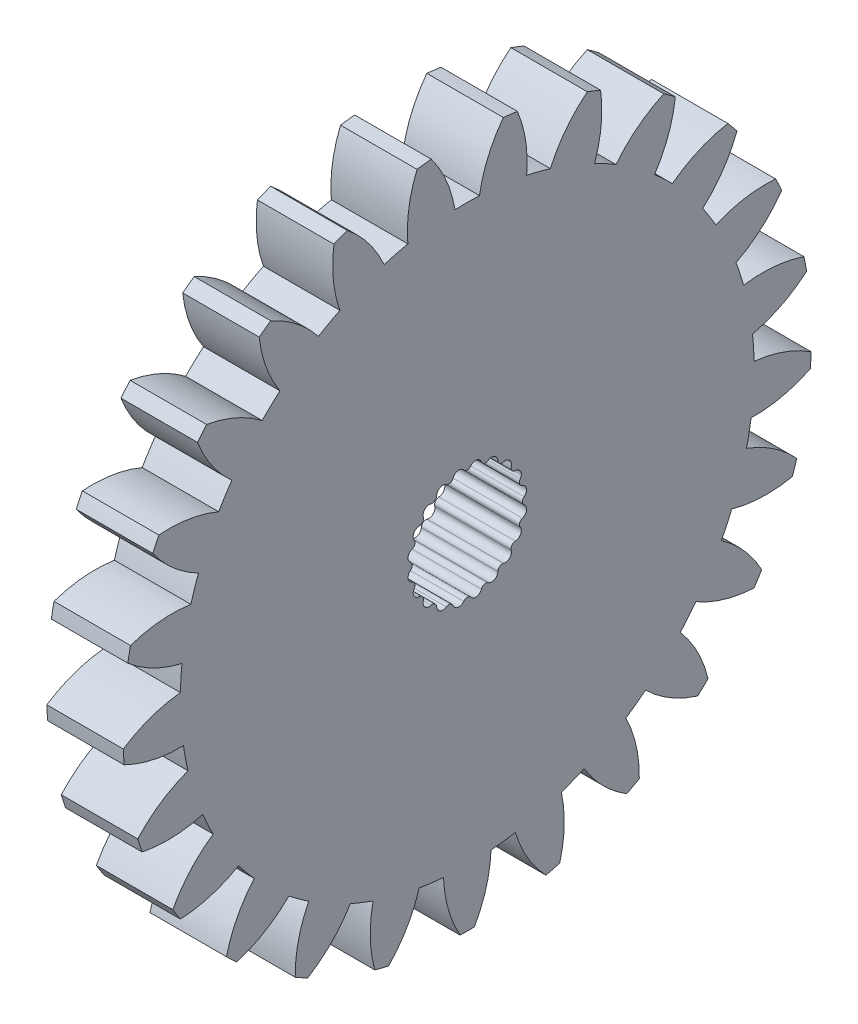
SolidWorks part; units mm, degrees
ref_plane "Plane1" through (0, 0, 0) normal (0, 0, 1) x (1, 0, 0)
ref_plane "Plane2" through (0, 0, 0) normal (0, 1, 0) x (1, 0, 0)
ref_plane "Plane3" through (0, 0, 0) normal (1, 0, 0) x (0, 0, -1)
other "Configuration Table"
sketch "HoldingSke" plane through (0, 0, 0) normal (0, 1, 0) x (1, 0, 0)
  line L0 (0, 0) -> (0.9063, -0.4226)
  line L1 (-15, 0) -> (100, 0) construction
  line L2 (0, 0) -> (-2.1039, 2.3779)
  line L3 (0, 0) -> (-11.863, 4.5341)
  line L4 (0, 0) -> (7.8269, 3.6497)
  line L5 (0, 0) -> (-46.8476, -17.4728)
  line L6 (0, 0) -> (-2.4869, -1.6779)
  line L7 (-2.1039, 2.3779) -> (8.6586, 51.2059)
  line L8 (-76.2, 54.61) -> (-75.3, 54.61)
  line L9 (-71.009, 38.7566) -> (-53.1078, 45.2721)
  line L10 (-76.2, 71.12) -> (104.1128, 71.12)
  line L11 (0, 0) -> (-3, 0)
  line L12 (-76.2, 101.6) -> (-76.162, 101.6)
  line L13 (24.9733, 27.94) -> (52.9518, 28.4284)
  line L14 (24.9733, 27.94) -> (24.9743, 27.94)
  line L15 (24.9733, 27.94) -> (100.4006, 29.5858)
  line L16 (-63.627, -1) -> (-12.827, -1)
  circle A0 centre (0, 0) radius 2.5
  circle A1 centre (0, 0) radius 11.249
  circle A2 centre (0, 0) radius 37.5
  circle A3 centre (0, 0) radius 2.5
  dimension "MHD" = 22.498
  dimension "Hub_dia" = 75
  dimension "Bore" = 5
  dimension "MBD" = 5
  dimension "Num_teeth" = 25
  dimension "Pitch" = 1
  dimension "Overall_len" = 50
  dimension "Show_teeth" = 25
  dimension "Thickness" = 3
  dimension "OAL" = 50.0001
  dimension "T_dim" = 0.9
  dimension "Ap" = 20
  dimension "H" = 19.05
  dimension "Pitch_radius" = 180.3128
  dimension "Width" = 3
  dimension "Backlash" = 0.038
  dimension "Addendum_fac" = 1
  dimension "Dedendum_fac" = 1.25
  dimension "Clearance_fac" = 0.25
  dimension "Dedendum_add" = 0.001
  dimension "Module" = 1
sketch "BasProSke" plane through (0, 0, 0) normal (0, 1, 0) x (1, 0, 0)
  line L0 (-10, 0) -> (60, 0) construction
  line L1 (0, 0) -> (0, 13.5)
  line L2 (0, 0) -> (3, 0)
  line L3 (3, 0) -> (3, 13.5)
  line L4 (3, 13.5) -> (0, 13.5)
  dimension "Thickness" = 3
  dimension "Diameter" = 27
revolve "Base-Revolve" add sketch "BasProSke" angle 360 about L0
sketch "TooCutSke" plane through (0, 0, 0) normal (1, 0, 0) x (0, 0, -1)
  line L1 (0, 0) -> (0, 107) construction
  line L2 (0, 0) -> (-0.8514, 12.471) construction
  line L3 (0, 0) -> (-3.1282, 24.7619) construction
  line L4 (-0.8514, 12.471) -> (-1.5641, 12.3809) construction
  arc A0 (0.4801, 11.2388) -> (-0.4801, 11.2388) centre (0, 0) ccw
  arc A1 (1.4322, 13.4494) -> (-1.4322, 13.4494) centre (0, 0) ccw
  circle A2 centre (0, 0) radius 12.5 construction
  circle A3 centre (0, 0) radius 11.7462 construction
  arc A4 (-0.4801, 11.2388) -> (-1.4322, 13.4494) centre (-5.4133, 10.4244) ccw
  arc A5 (1.4322, 13.4494) -> (0.4801, 11.2388) centre (5.4133, 10.4244) ccw
  dimension "Root_dia" = 22.498
  dimension "Overcut_dia" = 27.0508
  dimension "Pitch_dia" = 25
  dimension "Base_dia" = 23.4923
  dimension "Flank_rad" = 5
  dimension "Half_ang" = 7.2
  dimension "Half_CT" = 0.7184
extrude "ToothCut" cut sketch "TooCutSke" along normal through all
fillet "Breaks" [suppressed] radius 0.02
fillet "RootFillets" [suppressed] radius 0.251
pattern_circular "TeethCuts" count 25 every 14.4 about axis through (-10, 0, 0) along (1, 0, 0) of "ToothCut", "RootFillets", "Breaks"
sketch "HubNeaOneSke" plane through (0, 0, 0) normal (-1, 0, 0) x (0, 0, 1)
  circle A0 centre (0, 0) radius 11.249
  dimension "Diameter" = 22.498
extrude "HubNearOne" [suppressed] add sketch "HubNeaOneSke" along normal blind 47.0001
sketch "HubNeaBotSke" plane through (0, 0, 0) normal (-1, 0, 0) x (0, 0, 1)
  circle A0 centre (0, 0) radius 11.249
  dimension "Diameter" = 22.498
extrude "HubNearBoth" [suppressed] add sketch "HubNeaBotSke" along normal blind 23.5
ref_plane "FarPln" through (3, 0, 0) normal (1, 0, 0) x (0, 0, -1)
sketch "HubFarSke" plane through (3, 0, 0) normal (1, 0, 0) x (0, 0, -1)
  circle A0 centre (0, 0) radius 11.249
  dimension "Diameter" = 22.498
extrude "HubFar" [suppressed] add sketch "HubFarSke" along normal blind 23.5
sketch "BorSke" plane through (0, 0, 0) normal (1, 0, 0) x (0, 0, -1)
  circle A0 centre (0, 0) radius 2.5
  dimension "Diameter" = 5
extrude "Bore" [suppressed] cut sketch "BorSke" along normal mid plane 100.0001
sketch "KeySke" plane through (0, 0, 0) normal (1, 0, 0) x (0, 0, -1)
  line L0 (-1, 0) -> (-1, 3.4)
  line L1 (-1, 3.4) -> (1, 3.4)
  line L2 (1, 3.4) -> (1, 0)
  line L3 (0, 0) -> (0, 34) construction
  line L4 (-1, 0) -> (1, 0)
  dimension "Offset" = 3.4
  dimension "Width" = 2
extrude "Keyway" [suppressed] cut sketch "KeySke" along normal mid plane 100.0001
pattern_circular "Keyway2" [suppressed] count 2 every 90 about axis through (-10, 0, 0) along (1, 0, 0)
sketch "Sketch1" plane through (3, 0, 0) normal (1, 0, 0) x (0, 0, -1)
  arc A252 (1.6617, 1.6617) -> (1.423, 1.7224) centre (1.4913, 1.4913) ccw
  arc A253 (1.2704, 1.7486) -> (1.423, 1.7224) centre (1.3733, 1.8902) ccw
  arc A254 (1.1984, 1.8855) -> (1.2704, 1.7486) centre (1.3733, 1.8902) ccw
  arc A255 (1.1984, 1.8855) -> (1.0669, 2.0939) centre (0.9575, 1.8792) ccw
  arc A256 (1.0669, 2.0939) -> (0.8211, 2.0778) centre (0.9575, 1.8792) ccw
  arc A257 (0.6679, 2.0556) -> (0.8211, 2.0778) centre (0.722, 2.222) ccw
  arc A258 (0.557, 2.1636) -> (0.6679, 2.0556) centre (0.722, 2.222) ccw
  arc A259 (0.557, 2.1636) -> (0.3676, 2.3211) centre (0.3299, 2.0831) ccw
  arc A260 (0.3676, 2.3211) -> (0.1388, 2.2298) centre (0.3299, 2.0831) ccw
  arc A261 (0, 2.1614) -> (0.1388, 2.2298) centre (0, 2.3364) ccw
  arc A262 (-0.1388, 2.2298) -> (0, 2.1614) centre (0, 2.3364) ccw
  arc A263 (-0.1388, 2.2298) -> (-0.3676, 2.3211) centre (-0.3299, 2.0831) ccw
  arc A264 (-0.3676, 2.3211) -> (-0.557, 2.1636) centre (-0.3299, 2.0831) ccw
  arc A265 (-0.6679, 2.0556) -> (-0.557, 2.1636) centre (-0.722, 2.222) ccw
  arc A266 (-0.8211, 2.0778) -> (-0.6679, 2.0556) centre (-0.722, 2.222) ccw
  arc A267 (-0.8211, 2.0778) -> (-1.0669, 2.0939) centre (-0.9575, 1.8792) ccw
  arc A268 (-1.0669, 2.0939) -> (-1.1984, 1.8855) centre (-0.9575, 1.8792) ccw
  arc A269 (-1.2704, 1.7486) -> (-1.1984, 1.8855) centre (-1.3733, 1.8902) ccw
  arc A270 (-1.423, 1.7224) -> (-1.2704, 1.7486) centre (-1.3733, 1.8902) ccw
  arc A271 (-1.423, 1.7224) -> (-1.6617, 1.6617) centre (-1.4913, 1.4913) ccw
  arc A272 (-1.6617, 1.6617) -> (-1.7224, 1.423) centre (-1.4913, 1.4913) ccw
  arc A273 (-1.7486, 1.2704) -> (-1.7224, 1.423) centre (-1.8902, 1.3733) ccw
  arc A274 (-1.8855, 1.1984) -> (-1.7486, 1.2704) centre (-1.8902, 1.3733) ccw
  arc A275 (-1.8855, 1.1984) -> (-2.0939, 1.0669) centre (-1.8792, 0.9575) ccw
  arc A276 (-2.0939, 1.0669) -> (-2.0778, 0.8211) centre (-1.8792, 0.9575) ccw
  arc A277 (-2.0556, 0.6679) -> (-2.0778, 0.8211) centre (-2.222, 0.722) ccw
  arc A278 (-2.1636, 0.557) -> (-2.0556, 0.6679) centre (-2.222, 0.722) ccw
  arc A279 (-2.1636, 0.557) -> (-2.3211, 0.3676) centre (-2.0831, 0.3299) ccw
  arc A280 (-2.3211, 0.3676) -> (-2.2298, 0.1388) centre (-2.0831, 0.3299) ccw
  arc A281 (-2.1614, 0) -> (-2.2298, 0.1388) centre (-2.3364, 0) ccw
  arc A282 (-2.2298, -0.1388) -> (-2.1614, 0) centre (-2.3364, 0) ccw
  arc A283 (-2.2298, -0.1388) -> (-2.3211, -0.3676) centre (-2.0831, -0.3299) ccw
  arc A284 (-2.3211, -0.3676) -> (-2.1636, -0.557) centre (-2.0831, -0.3299) ccw
  arc A285 (-2.0556, -0.6679) -> (-2.1636, -0.557) centre (-2.222, -0.722) ccw
  arc A286 (-2.0778, -0.8211) -> (-2.0556, -0.6679) centre (-2.222, -0.722) ccw
  arc A287 (-2.0778, -0.8211) -> (-2.0939, -1.0669) centre (-1.8792, -0.9575) ccw
  arc A288 (-2.0939, -1.0669) -> (-2.0547, -1.1225) centre (-1.8792, -0.9575) ccw
  arc A290 (2.0547, 1.1225) -> (1.8855, 1.1984) centre (1.8792, 0.9575) ccw
  arc A291 (1.7486, 1.2704) -> (1.8855, 1.1984) centre (1.8902, 1.3733) ccw
  arc A292 (1.7224, 1.423) -> (1.7486, 1.2704) centre (1.8902, 1.3733) ccw
  arc A293 (1.7224, 1.423) -> (1.6617, 1.6617) centre (1.4913, 1.4913) ccw
  arc A294 (-1.6617, -1.6617) -> (-1.423, -1.7224) centre (-1.4913, -1.4913) ccw
  arc A295 (-1.2704, -1.7486) -> (-1.423, -1.7224) centre (-1.3733, -1.8902) ccw
  arc A296 (-1.1984, -1.8855) -> (-1.2704, -1.7486) centre (-1.3733, -1.8902) ccw
  arc A297 (-1.1984, -1.8855) -> (-1.0669, -2.0939) centre (-0.9575, -1.8792) ccw
  arc A298 (-1.0669, -2.0939) -> (-0.8211, -2.0778) centre (-0.9575, -1.8792) ccw
  arc A299 (-0.6679, -2.0556) -> (-0.8211, -2.0778) centre (-0.722, -2.222) ccw
  arc A300 (-0.557, -2.1636) -> (-0.6679, -2.0556) centre (-0.722, -2.222) ccw
  arc A301 (-0.557, -2.1636) -> (-0.3676, -2.3211) centre (-0.3299, -2.0831) ccw
  arc A302 (-0.3676, -2.3211) -> (-0.1388, -2.2298) centre (-0.3299, -2.0831) ccw
  arc A303 (0, -2.1614) -> (-0.1388, -2.2298) centre (0, -2.3364) ccw
  arc A304 (0.1388, -2.2298) -> (0, -2.1614) centre (0, -2.3364) ccw
  arc A305 (0.1388, -2.2298) -> (0.3676, -2.3211) centre (0.3299, -2.0831) ccw
  arc A306 (0.3676, -2.3211) -> (0.557, -2.1636) centre (0.3299, -2.0831) ccw
  arc A307 (0.6679, -2.0556) -> (0.557, -2.1636) centre (0.722, -2.222) ccw
  arc A308 (0.8211, -2.0778) -> (0.6679, -2.0556) centre (0.722, -2.222) ccw
  arc A309 (0.8211, -2.0778) -> (1.0669, -2.0939) centre (0.9575, -1.8792) ccw
  arc A310 (1.0669, -2.0939) -> (1.1984, -1.8855) centre (0.9575, -1.8792) ccw
  arc A311 (1.2704, -1.7486) -> (1.1984, -1.8855) centre (1.3733, -1.8902) ccw
  arc A312 (1.423, -1.7224) -> (1.2704, -1.7486) centre (1.3733, -1.8902) ccw
  arc A313 (1.423, -1.7224) -> (1.6617, -1.6617) centre (1.4913, -1.4913) ccw
  arc A314 (1.6617, -1.6617) -> (1.7224, -1.423) centre (1.4913, -1.4913) ccw
  arc A315 (1.7486, -1.2704) -> (1.7224, -1.423) centre (1.8902, -1.3733) ccw
  arc A316 (1.8855, -1.1984) -> (1.7486, -1.2704) centre (1.8902, -1.3733) ccw
  arc A317 (1.8855, -1.1984) -> (2.0939, -1.0669) centre (1.8792, -0.9575) ccw
  arc A318 (2.0939, -1.0669) -> (2.0778, -0.8211) centre (1.8792, -0.9575) ccw
  arc A319 (2.0556, -0.6679) -> (2.0778, -0.8211) centre (2.222, -0.722) ccw
  arc A320 (2.1636, -0.557) -> (2.0556, -0.6679) centre (2.222, -0.722) ccw
  arc A321 (2.1636, -0.557) -> (2.3211, -0.3676) centre (2.0831, -0.3299) ccw
  arc A322 (2.3211, -0.3676) -> (2.2298, -0.1388) centre (2.0831, -0.3299) ccw
  arc A323 (2.1614, 0) -> (2.2298, -0.1388) centre (2.3364, 0) ccw
  arc A324 (2.2298, 0.1388) -> (2.1614, 0) centre (2.3364, 0) ccw
  arc A325 (2.2298, 0.1388) -> (2.3211, 0.3676) centre (2.0831, 0.3299) ccw
  arc A326 (2.3211, 0.3676) -> (2.1636, 0.557) centre (2.0831, 0.3299) ccw
  arc A327 (2.0556, 0.6679) -> (2.1636, 0.557) centre (2.222, 0.722) ccw
  arc A328 (2.0778, 0.8211) -> (2.0556, 0.6679) centre (2.222, 0.722) ccw
  arc A329 (2.0778, 0.8211) -> (2.0939, 1.0669) centre (1.8792, 0.9575) ccw
  arc A330 (2.0939, 1.0669) -> (2.0547, 1.1225) centre (1.8792, 0.9575) ccw
  arc A332 (-2.0547, -1.1225) -> (-1.8855, -1.1984) centre (-1.8792, -0.9575) ccw
  arc A333 (-1.7486, -1.2704) -> (-1.8855, -1.1984) centre (-1.8902, -1.3733) ccw
  arc A334 (-1.7224, -1.423) -> (-1.7486, -1.2704) centre (-1.8902, -1.3733) ccw
  arc A335 (-1.7224, -1.423) -> (-1.6617, -1.6617) centre (-1.4913, -1.4913) ccw
extrude "Cut-Extrude1" cut sketch "Sketch1" against normal through all and the other way through all
equation "' \"Module@HoldingSke\" = 6.35"
equation "' \"Num_teeth@HoldingSke\" = 12"
equation "' \"Ap@HoldingSke\" =  20"
equation "' \"Ap@HoldingSke\" = 20"
equation "' \"Width@HoldingSke\" = 0.5 * 25.4"
equation "' \"Hub_dia@HoldingSke\"= 1 * 25.4"
equation "' \"Hub_dia@HoldingSke\" = 1 * 25.4"
equation "' \"Overall_len@HoldingSke\" = 1.0 * 25.4"
equation "' \"Bore@HoldingSke\" = 0.75 * 25.4"
equation "' \"T_dim@HoldingSke\" = 0.1 * 25.4"
equation "' \"Width@KeySke\" = 0.25 * 25.4"
equation "' \"Show_teeth@HoldingSke\" = 13"
equation "' \"Backlash@HoldingSke\" = 0.009 * 25.4"
equation "' \"Addendum_fac@HoldingSke\" = 1.0"
equation "' \"Dedendum_fac@HoldingSke\" = 1.25"
equation "' \"Dedendum_add@HoldingSke\" = 0.00005 * 25.4"
equation "' \"Clearance_fac@HoldingSke\" = 0.25"
equation "\"Pitch@HoldingSke\" = 1 / \"Module@HoldingSke\""
equation "\"Overcut_dia@TooCutSke\" = (\"Num_teeth@HoldingSke\" + 2 * \"Addendum_fac@HoldingSke\") / \"Pitch@HoldingSke\" + 0.002 * 25.4"
equation "\"Pitch_dia@TooCutSke\" = \"Num_teeth@HoldingSke\" / \"Pitch@HoldingSke\""
equation "\"Base_dia@TooCutSke\" = \"Num_teeth@HoldingSke\" / \"Pitch@HoldingSke\" * cos((\"Ap@HoldingSke\"  * 3.14159265 / 180))"
equation "\"Root_dia@TooCutSke\" = (\"Num_teeth@HoldingSke\" + 2) / \"Pitch@HoldingSke\" - 2 * (\"Addendum_fac@HoldingSke\" + \"Dedendum_fac@HoldingSke\") / \"Pitch@HoldingSke\" - \"Dedendum_add@HoldingSke\" * 2"
equation "\"Half_ang@TooCutSke\" = 180 / \"Num_teeth@HoldingSke\""
equation "\"Half_CT@TooCutSke\" = \"Num_teeth@HoldingSke\" / \"Pitch@HoldingSke\" * sin((3.14159265 / 2 / \"Num_teeth@HoldingSke\")) / 2 - 7 * \"Backlash@HoldingSke\" / 4"
equation "\"Flank_rad@TooCutSke\" = \"Num_teeth@HoldingSke\" / \"Pitch@HoldingSke\" / 5"
equation "\"Radius@RootFillets\" = \"Clearance_fac@HoldingSke\" / \"Pitch@HoldingSke\" + \"Dedendum_add@HoldingSke\""
equation "\"Break_rad@Breaks\" = 0.02 / \"Pitch@HoldingSke\""
equation "\"Thickness@HoldingSke\" = \"Width@HoldingSke\""
equation "\"OAL@HoldingSke\" = \"Thickness@HoldingSke\""
equation "\"MHD@HoldingSke\" = (\"Num_teeth@HoldingSke\" + 2) / \"Pitch@HoldingSke\" - 2 * (\"Addendum_fac@HoldingSke\" + \"Dedendum_fac@HoldingSke\")  / \"Pitch@HoldingSke\" - \"Dedendum_add@HoldingSke\" * 2"
equation "\"MBD@HoldingSke\" = (\"Num_teeth@HoldingSke\" + 2) / \"Pitch@HoldingSke\" - 2 * (\"Addendum_fac@HoldingSke\" + \"Dedendum_fac@HoldingSke\")  / \"Pitch@HoldingSke\" - \"Dedendum_add@HoldingSke\" * 2 - 0.002 * 25.4"
equation "\"MHD@HoldingSke\" = ((sgn( \"MHD@HoldingSke\" - \"Hub_dia@HoldingSke\" )-1)*( \"MHD@HoldingSke\" - \"Hub_dia@HoldingSke\" ))/-2+ \"Hub_dia@HoldingSke\""
equation "\"MBD@HoldingSke\" = ((sgn( \"MBD@HoldingSke\" - \"Bore@HoldingSke\" )-1)*( \"MBD@HoldingSke\" - \"Bore@HoldingSke\" ))/-2+ \"Bore@HoldingSke\""
equation "\"OAL@HoldingSke\" = ((sgn( \"OAL@HoldingSke\" - \"Overall_len@HoldingSke\" )+1)*( \"OAL@HoldingSke\" - \"Overall_len@HoldingSke\" ))/2 + \"Overall_len@HoldingSke\" + 0.000002 * 25.4"
equation "\"Num_teeth@TeethCuts\" = int( \"Show_teeth@HoldingSke\" ) + 1"
equation "\"Num_teeth@TeethCuts\" = ((sgn( \"Num_teeth@TeethCuts\" - \"Num_teeth@HoldingSke\" )-1)*( \"Num_teeth@TeethCuts\" - \"Num_teeth@HoldingSke\" ))/-2+ \"Num_teeth@HoldingSke\""
equation "\"Num_teeth@TeethCuts\" = ((sgn( \"Num_teeth@TeethCuts\" - 2.0)+1)*( \"Num_teeth@TeethCuts\" - 2.0))/2 +2.0"
equation "\"Angle@TeethCuts\" = 360.0 / \"Num_teeth@HoldingSke\""
equation "\"Diameter@BasProSke\" = (\"Num_teeth@HoldingSke\" + 2 * \"Addendum_fac@HoldingSke\") / \"Pitch@HoldingSke\""
equation "\"Thickness@BasProSke\"  = \"Thickness@HoldingSke\""
equation "' \"Fillet_rad@BasProSke\" =  \"Thickness@HoldingSke\" * 0.05"
equation "' \"Fillet_rad@BasProSke\" = \"Thickness@HoldingSke\" * 0.05"
equation "\"MHD@HoldingSke\" = ((sgn( \"MHD@HoldingSke\" - \"Root_dia@TooCutSke\" )-1)*( \"MHD@HoldingSke\" - \"Root_dia@TooCutSke\" ))/-2+ \"Root_dia@TooCutSke\""
equation "\"Diameter@HubNeaOneSke\" = \"MHD@HoldingSke\""
equation "\"Length@HubNearOne\" = \"OAL@HoldingSke\" - \"Thickness@BasProSke\""
equation "\"Diameter@HubNeaBotSke\" = \"MHD@HoldingSke\""
equation "\"Length@HubNearBoth\" = ( \"OAL@HoldingSke\" - \"Thickness@BasProSke\" ) / 2.0"
equation "\"Thickness@FarPln\" = \"Thickness@BasProSke\""
equation "\"Diameter@HubFarSke\" = \"MHD@HoldingSke\""
equation "\"Length@HubFar\" = ( \"OAL@HoldingSke\" - \"Thickness@BasProSke\" ) / 2.0"
equation "\"D1@Bore\" = \"OAL@HoldingSke\" * 2.0"
equation "\"D1@Keyway\" = \"OAL@HoldingSke\" * 2.0"
equation "\"Offset@KeySke\" = \"T_dim@HoldingSke\" + \"MBD@HoldingSke\" / 2.0"
